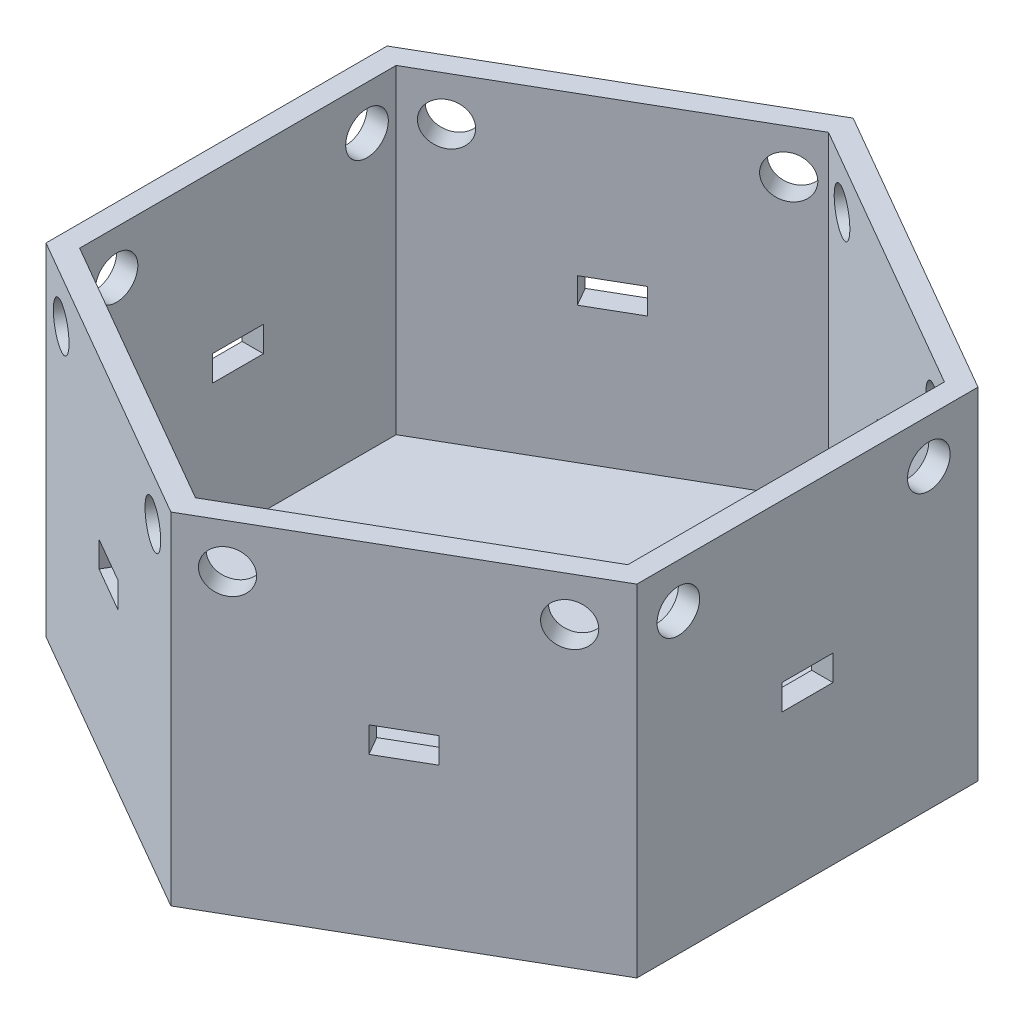
SolidWorks part; units mm, degrees
ref_plane "Front Plane" through (0, 0, 0) normal (0, 0, 1) x (1, 0, 0)
ref_plane "Top Plane" through (0, 0, 0) normal (0, 1, 0) x (1, 0, 0)
ref_plane "Right Plane" through (0, 0, 0) normal (1, 0, 0) x (0, 0, -1)
sketch "Sketch1" plane through (0, 0, 0) normal (0, 1, 0) x (1, 0, 0)
  line L1 (34.641, 20) -> (0, 40)
  line L2 (0, 40) -> (-34.641, 20)
  line L3 (-34.641, 20) -> (-34.641, -20)
  line L4 (-34.641, -20) -> (0, -40)
  line L5 (0, -40) -> (34.641, -20)
  line L6 (34.641, -20) -> (34.641, 20)
  dimension "D1" = 40
extrude "Boss-Extrude1" add sketch "Sketch1" along normal blind 40
shell "Shell1" thickness 2.5
sketch "Sketch2" plane through (0, 0, 0) normal (0, -1, 0) x (1, 0, 0)
  circle A0 centre (0, 0) radius 5
  dimension "D1" = 10
extrude "Cut-Extrude1" cut sketch "Sketch2" against normal blind 40 contours A0
sketch "Sketch3" plane through (-34.641, 0, 0) normal (-1, 0, 0) x (0, 0, 1)
  line L6 (-3, 21) -> (3, 21)
  line L7 (-3, 21) -> (-3, 19)
  line L8 (-3, 19) -> (3, 19)
  line L9 (3, 21) -> (3, 19)
  line L10 (-3, 21) -> (3, 19) construction
  line L11 (-3, 19) -> (3, 21) construction
  circle A0 centre (-15.1374, 34.8383) radius 2.5
  circle A1 centre (14.2324, 34.8383) radius 2.5
  point P15 (0, 20)
  dimension "D1" = 5
  dimension "D2" = 5
  dimension "D3" = 6
  dimension "D4" = 2
extrude "Cut-Extrude2" cut sketch "Sketch3" against normal blind 2.5 contours A1 | A0
sketch "Sketch4" plane through (-34.641, 0, 0) normal (-1, 0, 0) x (0, 0, 1)
  line L7 (-3, 18.5) -> (3, 18.5)
  line L8 (-3, 18.5) -> (-3, 21.5)
  line L9 (-3, 21.5) -> (3, 21.5)
  line L10 (3, 18.5) -> (3, 21.5)
  dimension "D1" = 6
  dimension "D2" = 3
extrude "Cut-Extrude3" cut sketch "Sketch4" against normal blind 40 contours L8 L7 L10 L9
pattern_circular "CirPattern1" count 6 over 360 about axis through (0, 0, 0) along (0, 1, 0) of "Cut-Extrude2", "Cut-Extrude3"
